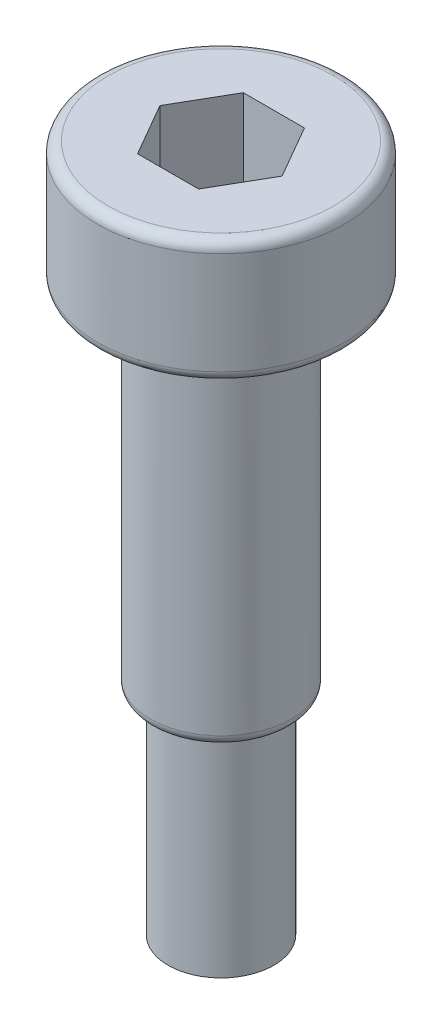
SolidWorks part; units mm, degrees
ref_plane "前视基准面" through (0, 0, 0) normal (0, 0, 1) x (1, 0, 0)
ref_plane "上视基准面" through (0, 0, 0) normal (0, 1, 0) x (1, 0, 0)
ref_plane "右视基准面" through (0, 0, 0) normal (1, 0, 0) x (0, 0, -1)
other "Configuration Table"
sketch "草图1" plane through (0, 0, 0) normal (0, 0, 1) x (1, 0, 0)
  line L0 (0, 0) -> (-1.5, 0)
  line L1 (-1.5, 0) -> (-1.5, 6)
  line L2 (-1.5, 6) -> (-2, 6)
  line L3 (-2, 6) -> (-2, 16)
  line L4 (-2, 16) -> (-3.5, 16)
  line L5 (-3.5, 16) -> (-3.5, 19.5)
  line L6 (-3.5, 19.5) -> (0, 19.5)
  line L7 (0, 19.5) -> (0, 0) construction
  line L8 (0, 0) -> (0, 19.5)
  dimension "D1" = 7
  dimension "D2" = 10
  dimension "D3" = 4
  dimension "D4" = 3.5
  dimension "D5" = 3
  dimension "D6" = 6
revolve "旋转1" add sketch "草图1" angle 360 about L7
cosmetic thread "装饰螺纹线1" parameters "D2"=2.459
fillet "圆角1" radius 0.3 3 edges at (-3.5, 19.5, 0) (-2, 6, 0) (-3.5, 16, 0)
sketch "草图2" plane through (0, 19.5, 0) normal (0, 1, 0) x (1, 0, 0)
  line L1 (0.866, -1.5) -> (1.7321, 0)
  line L2 (1.7321, 0) -> (0.866, 1.5)
  line L3 (0.866, 1.5) -> (-0.866, 1.5)
  line L4 (-0.866, 1.5) -> (-1.7321, 0)
  line L5 (-1.7321, 0) -> (-0.866, -1.5)
  line L6 (-0.866, -1.5) -> (0.866, -1.5)
  circle A0 centre (0, 0) radius 1.5 construction
  dimension "D1" = 3
extrude "切除-拉伸1" cut sketch "草图2" against normal blind 2.4
